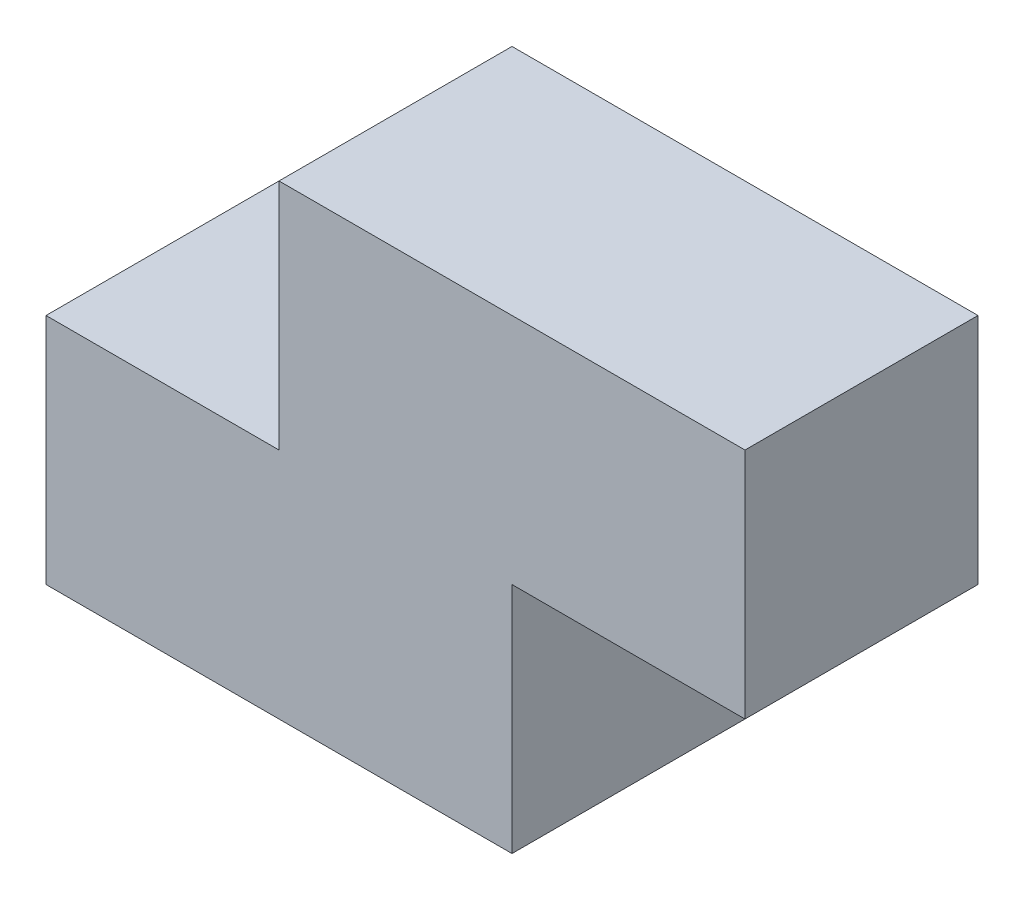
SolidWorks part; units mm, degrees
ref_plane "前基準面" through (0, 0, 0) normal (0, 0, 1) x (1, 0, 0)
ref_plane "上基準面" through (0, 0, 0) normal (0, 1, 0) x (1, 0, 0)
ref_plane "右基準面" through (0, 0, 0) normal (1, 0, 0) x (0, 0, -1)
sketch "草圖1" plane through (0, 0, 0) normal (0, 1, 0) x (1, 0, 0)
  line L0 (0, 0) -> (60, 0)
  line L1 (60, 0) -> (60, -30)
  line L2 (60, -30) -> (0, -30)
  line L3 (0, -30) -> (0, 0)
  dimension "D1" = 60
  dimension "D2" = 30
extrude "填料-伸長1" add sketch "草圖1" along normal blind 30
sketch "草圖2" plane through (0, 30, 0) normal (0, 1, 0) x (1, 0, 0)
  line L0 (60, 0) -> (30, 0)
  line L1 (30, 0) -> (30, -30)
  line L2 (0, -30) -> (60, -30) construction
  line L3 (30, -30) -> (60, -30)
  line L4 (60, -30) -> (60, 0)
  dimension "D1" = 30
extrude "填料-伸長2" add sketch "草圖2" along normal blind 30
sketch "草圖3" plane through (60, 0, 0) normal (1, 0, 0) x (0, 0, -1)
  line L0 (-30, 60) -> (0, 60)
  line L1 (0, 60) -> (0, 30)
  line L2 (0, 30) -> (-30, 30)
  line L3 (-30, 60) -> (-30, 0) construction
  line L4 (-30, 30) -> (-30, 60)
extrude "填料-伸長3" add sketch "草圖3" along normal blind 30
